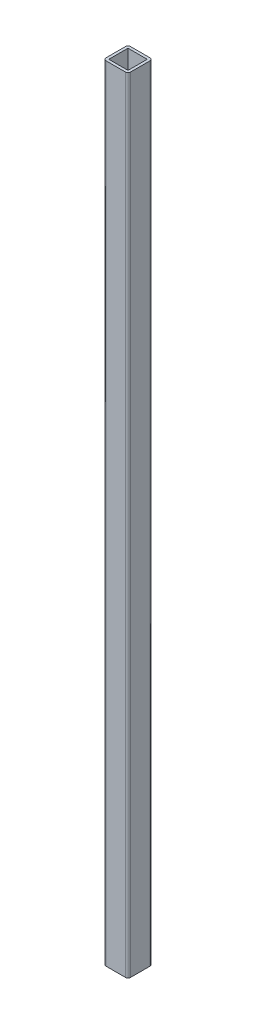
SolidWorks part; units mm, degrees
material "Plain Carbon Steel"
ref_plane "Front Plane" through (0, 0, 0) normal (0, 0, 1) x (1, 0, 0)
ref_plane "Top Plane" through (0, 0, 0) normal (0, 1, 0) x (1, 0, 0)
ref_plane "Right Plane" through (0, 0, 0) normal (1, 0, 0) x (0, 0, -1)
sketch "Sketch1" plane through (0, 0, 0) normal (0, 1, 0) x (1, 0, 0)
  line L1 (2.8, 0) -> (22.8, 0)
  line L2 (0, -2.8) -> (0, -22.8)
  line L3 (2.8, -25.6) -> (22.8, -25.6)
  line L4 (25.6, -2.8) -> (25.6, -22.8)
  arc A0 (22.8, 0) -> (25.6, -2.8) centre (22.8, -2.8) cw
  arc A1 (22.8, -25.6) -> (25.6, -22.8) centre (22.8, -22.8) ccw
  arc A2 (0, -22.8) -> (2.8, -25.6) centre (2.8, -22.8) ccw
  arc A3 (2.8, 0) -> (0, -2.8) centre (2.8, -2.8) ccw
  point P7 (25.6, 0)
  point P10 (25.6, -25.6)
  point P15 (0, 0)
  dimension "D2" = 2.8
  dimension "D1" = 25.6
extrude "Boss-Extrude1" add sketch "Sketch1" along normal blind 816
sketch "Sketch3" plane through (0, 0, 0) normal (0, -1, 0) x (-1, 0, 0)
  line L4 (-2.8, -2.8) -> (-22.8, -2.8)
  line L5 (-2.8, -2.8) -> (-2.8, -22.8)
  line L6 (-2.8, -22.8) -> (-22.8, -22.8)
  line L7 (-22.8, -2.8) -> (-22.8, -22.8)
  line L8 (-2.8, -2.8) -> (-22.8, -22.8) construction
  line L9 (-2.8, -22.8) -> (-22.8, -2.8) construction
  point P6 (-12.8, -12.8)
extrude "Cut-Extrude1" cut sketch "Sketch3" against normal blind 816
